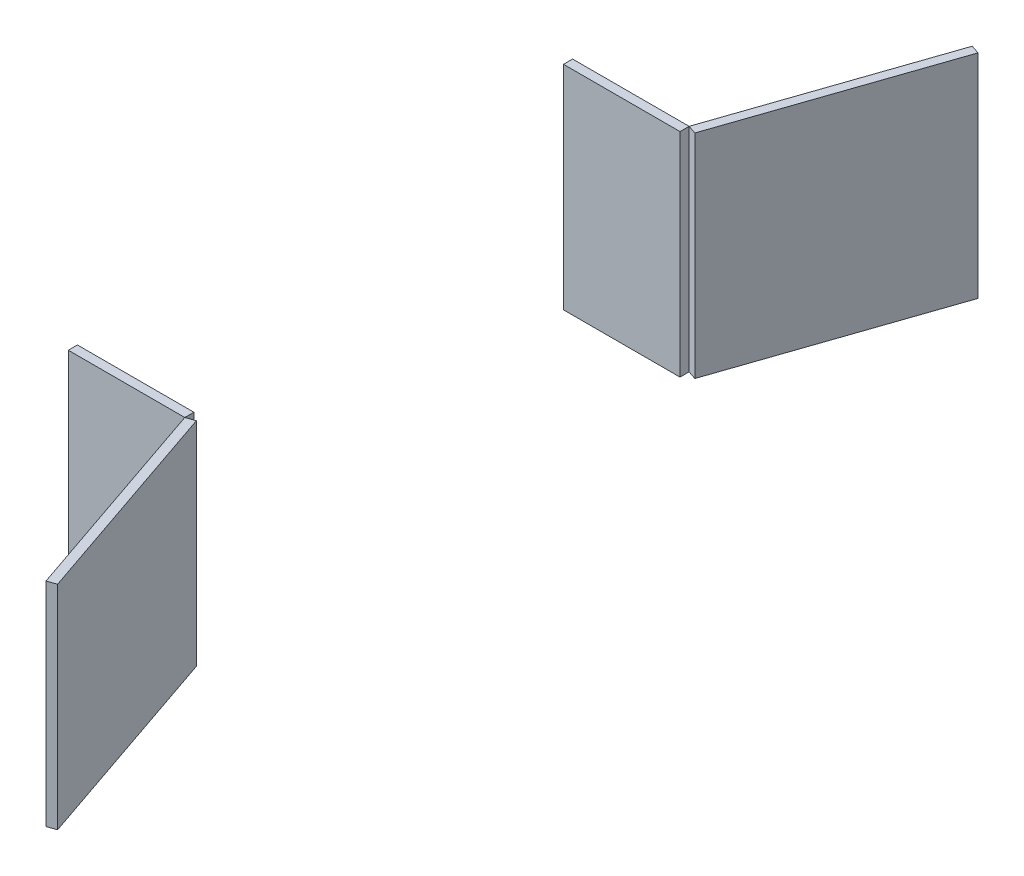
SolidWorks part; units mm, degrees
ref_plane "Alzado" through (0, 0, 0) normal (0, 0, 1) x (1, 0, 0)
ref_plane "Planta" through (0, 0, 0) normal (0, 1, 0) x (1, 0, 0)
ref_plane "Vista lateral" through (0, 0, 0) normal (1, 0, 0) x (0, 0, -1)
sketch "Croquis1" plane through (0, 0, 0) normal (0, 1, 0) x (1, 0, 0)
  line L0 (23.7643, 152.45) -> (0, 83)
  line L1 (-38.3574, 83) -> (0, 83)
  line L2 (-38.3574, 83) -> (-38.3574, 80)
  line L3 (-38.3574, 80) -> (0, 80)
  line L4 (0, 83) -> (0, 80)
  line L5 (-38.3574, 83) -> (0, 80) construction
  line L6 (-38.3574, 80) -> (0, 83) construction
  line L7 (-38.3574, -80) -> (0, -80)
  line L8 (-38.3574, -80) -> (-38.3574, -83)
  line L9 (-38.3574, -83) -> (0, -83)
  line L10 (0, -80) -> (0, -83)
  line L11 (-38.3574, -80) -> (0, -83) construction
  line L12 (-38.3574, -83) -> (0, -80) construction
  line L17 (23.7643, 152.45) -> (26.6027, 151.4788)
  line L18 (0, 83) -> (2.8384, 82.0288)
  line L23 (26.6027, 151.4788) -> (2.8384, 82.0288)
  line L24 (23.7643, 152.45) -> (2.8384, 82.0288) construction
  line L25 (0, 83) -> (26.6027, 151.4788) construction
  line L26 (2.8384, -82.0288) -> (0, -83)
  line L27 (2.8384, -82.0288) -> (26.6027, -151.4788)
  line L28 (0, -83) -> (23.7643, -152.45)
  line L29 (26.6027, -151.4788) -> (23.7643, -152.45)
  line L30 (2.8384, -82.0288) -> (23.7643, -152.45) construction
  line L31 (0, -83) -> (26.6027, -151.4788) construction
  line L33 (-89.5098, 152.45) -> (89.5098, 152.45) construction
  line L34 (-89.5098, 152.45) -> (-89.5098, -152.45) construction
  line L35 (-89.5098, -152.45) -> (89.5098, -152.45) construction
  line L36 (89.5098, 152.45) -> (89.5098, -152.45) construction
  line L37 (-89.5098, 152.45) -> (89.5098, -152.45) construction
  line L38 (-89.5098, -152.45) -> (89.5098, 152.45) construction
  point P0 (-19.1787, 81.5)
  point P5 (-19.1787, -81.5)
  point P10 (0, 0)
  point P11 (13.3013, 117.2394)
  point P12 (13.3013, -117.2394)
  point P13 (0, 0)
  point P23 (0, 0)
  dimension "D1" = 304.9
  dimension "D2" = 160
  dimension "D3" = 80
  dimension "D4" = 3
extrude "Saliente-Extruir1" add sketch "Croquis1" along normal blind 70 contours L10 L7 L8 L9 | L29 L27 L26 L28 | L4 L1 L2 L3 | L23 L17 L0 L18
sketch "Croquis2" plane through (0, 0, 0) normal (0, 1, 0) x (1, 0, 0)
  line L1 (305.6165, 152.5) -> (-202.5286, 152.5)
  line L2 (305.6165, 152.5) -> (305.6165, -151.4)
  line L3 (305.6165, -151.4) -> (-202.5286, -151.4)
  line L4 (-202.5286, 152.5) -> (-202.5286, -151.4)
  line L5 (305.6165, 152.5) -> (-202.5286, -151.4) construction
  line L6 (305.6165, -151.4) -> (-202.5286, 152.5) construction
  point P0 (51.5439, 0.55)
  dimension "D1" = 303.9
  dimension "D2" = 0.05
equation "\"D1@Croquis1\"=\"ancho_tot\"-(\"GROSOR_PARED_IMPRESA\"+\"TOLERANCIA\")*2"
equation "\"venesta\"= 4'grosor de la venesta"
equation "\"policarbonato\"= 4'grosor del policarbonato"
equation "\"carton_trupan\"= 3'grosor del carton trupan caso laser"
equation "\"ancho_tot\"= 310'ancho tot sin llantas"
equation "\"largo_tot\"= 400'largo tot sin camera"
equation "\"alto_estimado\"= 300'alto estimado sin lidar"
equation "\"altoparaqpaselabotella\"= 75'alto estimado para que encaje la botella"
equation "\"alturaruedaloca\"= 22"
equation "\"anchoruedaloca\"= 35"
equation "\"anchopiso1motorybaterias\"= 150"
equation "\"dist-pisorampa\"= 5"
equation "\"anchoultimopiso\"= 170"
equation "\"paredtrasera\"= 100"
equation "\"agarradorcanasta\"= 275'recolector"
equation "\"alturapiso1y2\"= 80"
equation "\"alturapiso2y3\"= 80"
equation "\"GROSOR_PARED_IMPRESA\"= 2.5"
equation "\"TOLERANCIA\"= 0.05"
equation "\"APERTURA_BOTELLA\"= 160"
equation "\"D2@Croquis1\"=\"APERTURA_BOTELLA\""
equation "\"D3@Croquis1\"=\"APERTURA_BOTELLA\"/2"
equation "\"D4@Croquis1\"=\"carton_trupan\""
equation "\"D1@Croquis2\"=\"ancho_tot\"-(\"carton_trupan\"+\"TOLERANCIA\")*2"
equation "\"D2@Croquis2\"=\"TOLERANCIA\""
